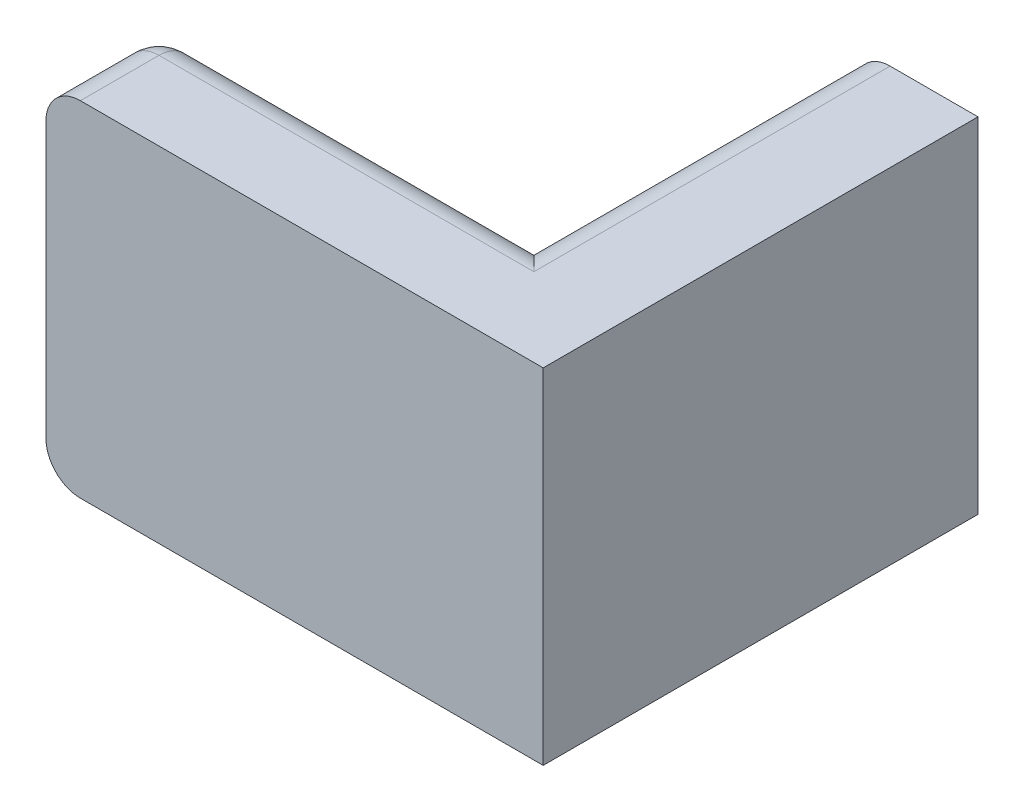
SolidWorks part; units mm, degrees
ref_plane "Front Plane" through (0, 0, 0) normal (0, 0, 1) x (1, 0, 0)
ref_plane "Top Plane" through (0, 0, 0) normal (0, 1, 0) x (1, 0, 0)
ref_plane "Right Plane" through (0, 0, 0) normal (1, 0, 0) x (0, 0, -1)
sketch "Sketch1" plane through (0, 0, 0) normal (0, 1, 0) x (1, 0, 0)
  line L0 (0, 0) -> (72.2072, 0)
  line L1 (72.2072, 0) -> (72.2072, 63.1479)
  line L2 (72.2072, 63.1479) -> (54.4409, 63.1479)
  line L3 (54.4409, 63.1479) -> (54.4409, 16.4146)
  line L4 (54.4409, 16.4146) -> (0, 16.4146)
  line L5 (0, 16.4146) -> (0, 0)
extrude "Boss-Extrude1" add sketch "Sketch1" along normal blind 50
fillet "Fillet2" radius 5 7 edges at (54.4409, 50, -39.7812) (54.4409, 0, -39.7812) (27.2204, 50, -16.4146) (0, 50, -8.2073) (0, 25, -16.4146) (0, 0, -8.2073) (27.2204, 0, -16.4146)
